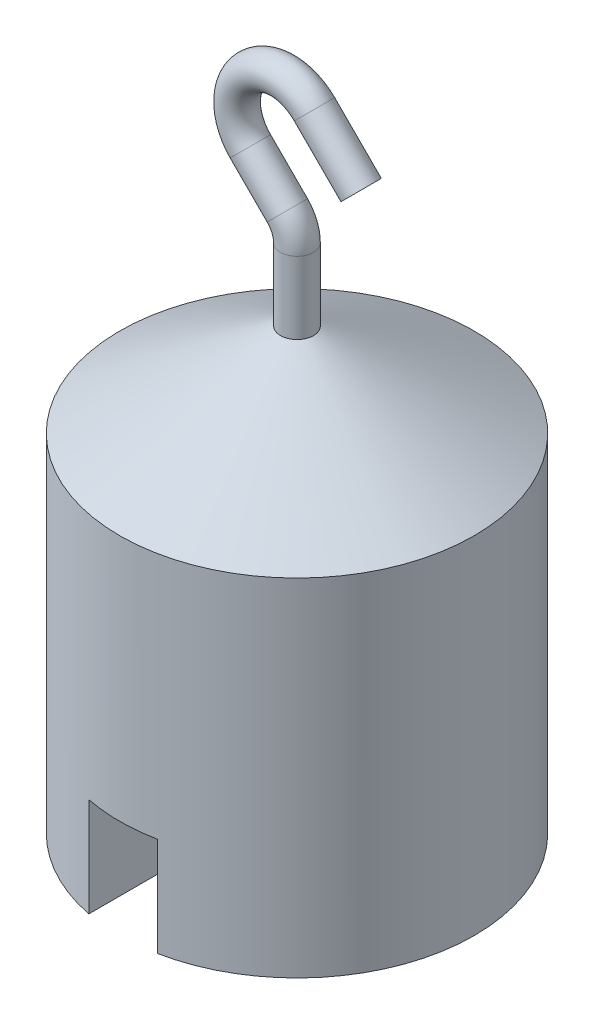
SolidWorks part; units mm, degrees
ref_plane "Front Plane" through (0, 0, 0) normal (0, 0, 1) x (1, 0, 0)
ref_plane "Top Plane" through (0, 0, 0) normal (0, 1, 0) x (1, 0, 0)
ref_plane "Right Plane" through (0, 0, 0) normal (1, 0, 0) x (0, 0, -1)
sketch "Sketch1" plane through (0, 0, 0) normal (0, 0, 1) x (1, 0, 0)
  line L0 (0, 0) -> (0, 42)
  line L1 (0, 42) -> (19.5, 53.2583)
  line L2 (19.5, 53.2583) -> (21.5, 53.2583)
  line L3 (21.5, 53.2583) -> (21.5, 0)
  line L4 (21.5, 0) -> (0, 0)
  dimension "D1" = 42
  dimension "D2" = 2
  dimension "D3" = 120
  dimension "D4" = 21.5
revolve "Revolve1" add sketch "Sketch1" angle 360 about L3
sketch "Sketch2" plane through (0, 53.2583, 0) normal (0, 1, 0) x (1, 0, 0)
  circle A0 centre (21.5, 0) radius 2
  dimension "D1" = 4
sketch "Sketch3" plane through (0, 0, 0) normal (0, 0, 1) x (1, 0, 0)
  line L0 (20.3284, 64.8299) -> (15.8431, 69.3152)
  line L1 (23.5, 53.2583) -> (19.5, 53.2583) construction
  line L2 (23.6213, 77.0934) -> (29.2782, 71.4365)
  line L3 (21.5, 53.2583) -> (21.5, 62.0015)
  line L4 (0, 0) -> (43, 0) construction
  arc A0 (15.8431, 69.3152) -> (23.6213, 77.0934) centre (19.7322, 73.2043) cw
  arc A1 (20.3284, 64.8299) -> (21.5, 62.0015) centre (17.5, 62.0015) cw
  point P12 (21.5, 63.6583)
  dimension "D3" = 5.5
  dimension "D6" = 4
  dimension "D1" = 45
  dimension "D2" = 8
  dimension "D4" = 8
  dimension "D5" = 10.4
sweep "Sweep6" add profiles "Sketch2" path "Sketch3"
sketch "Sketch10" plane through (0, 0, 0) normal (0, 0, 1) x (1, 0, 0)
  line L0 (0, 0) -> (43, 0) construction
  line L1 (17.35, 0) -> (25.65, 0)
  line L2 (17.35, 0) -> (17.35, 12)
  line L3 (17.35, 12) -> (25.65, 12)
  line L4 (25.65, 0) -> (25.65, 12)
  line L5 (21.5, 12) -> (21.5, 0) construction
  line L6 (0, 0) -> (43, 0) construction
  point P12 (21.5, 0)
  dimension "D1" = 12
  dimension "D2" = 8.3
extrude "Cut-Extrude1" cut sketch "Sketch10" against normal through all both and the other way through all
sketch "Sketch11" plane through (25.65, 0, 0) normal (-1, 0, 0) x (0, 0, 1)
  line L0 (0, -23.65) -> (0, 23.65) construction
  line L1 (-21.0957, 0) -> (21.0957, 0) construction
  circle A0 centre (0, 4.5) radius 1.5
  dimension "D1" = 3
  dimension "D2" = 4.5
extrude "Boss-Extrude1" add sketch "Sketch11" along normal up to next
sketch "Sketch12" plane through (0, 0, 0) normal (0, 0, 1) x (1, 0, 0)
  line L0 (23.5, 53.2583) -> (44.511, 74.2693) construction
  line L1 (23.5, 53.2583) -> (46.6392, 53.2583) construction
  dimension "D1" = 45
ref_plane "Plane1" through (0, 0, 0) normal (-1, 0, 0) x (0, 0, 1)
sketch "Sketch13" plane through (0, 0, 0) normal (-1, 0, 0) x (0, 0, 1)
  line L0 (0, 27) -> (0, 0) construction
  line L1 (-7.5, 33) -> (7.5, 33)
  line L2 (-7.5, 33) -> (-7.5, 27)
  line L3 (-7.5, 27) -> (7.5, 27)
  line L4 (7.5, 33) -> (7.5, 27)
  line L5 (21.5, 42) -> (-21.5, 42) construction
  dimension "D1" = 15
  dimension "D2" = 6
  dimension "D3" = 9
extrude "Cut-Extrude2" cut sketch "Sketch13" against normal blind 1.25
sketch "Sketch14" plane through (1.25, 0, 0) normal (-1, 0, 0) x (0, 0, 1)
  line L0 (-7.2241, 28) -> (7.2241, 28) construction
  line L1 (-7.2241, 28) -> (-7.2241, 27) construction
  line L2 (7.2241, 28) -> (7.2241, 27) construction
  line L3 (7.2241, 27) -> (-7.2241, 27) construction
  line L4 (4.3978, 29.2) -> (6.4889, 29.2) construction
  text T0 "500"
  text T1 "0" font "Century Gothic" height in points 8
  dimension "D1" = 1
  dimension "D2" = 1.2
extrude "Cut-Extrude3" cut sketch "Sketch14" against normal blind 0.5
